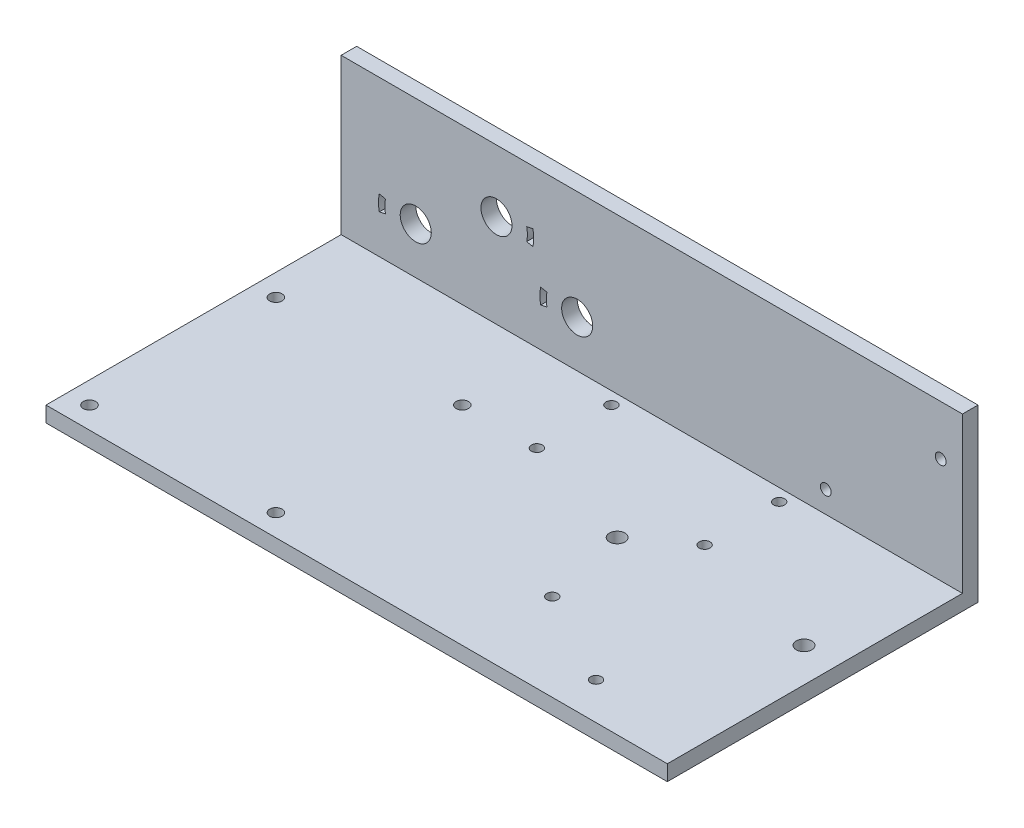
SolidWorks part; units mm, degrees
ref_plane "Front Plane" through (0, 0, 0) normal (0, 0, 1) x (1, 0, 0)
ref_plane "Top Plane" through (0, 0, 0) normal (0, 1, 0) x (1, 0, 0)
ref_plane "Right Plane" through (0, 0, 0) normal (1, 0, 0) x (0, 0, -1)
sketch "Sketch1" plane through (0, 0, 0) normal (0, 1, 0) x (1, 0, 0)
  line L1 (100, -50) -> (-100, -50)
  line L2 (100, -50) -> (100, 50)
  line L3 (100, 50) -> (-100, 50)
  line L4 (-100, -50) -> (-100, 50)
  line L5 (100, -50) -> (-100, 50) construction
  line L6 (100, 50) -> (-100, -50) construction
  point P0 (0, 0)
  dimension "D1" = 200
  dimension "D2" = 100
extrude "Boss-Extrude1" add sketch "Sketch1" along normal blind 5
sketch "Sketch2" plane through (0, 5, 0) normal (0, 1, 0) x (1, 0, 0)
  line L0 (100, -50) -> (100, 50) construction
  line L1 (-100, 50) -> (100, 50)
  line L2 (-100, 50) -> (-100, 45)
  line L3 (-100, 45) -> (100, 45)
  line L4 (100, 50) -> (100, 45)
  dimension "D1" = 5
extrude "Boss-Extrude2" add sketch "Sketch2" along normal blind 50
sketch "Sketch3" plane through (0, 0, -50) normal (0, 0, -1) x (-1, 0, 0)
  line L0 (-93, 12) -> (-56, 39) construction
  line L1 (-93, 39) -> (-56, 39) construction
  line L2 (-93, 39) -> (-93, 12) construction
  line L3 (-93, 12) -> (-56, 12) construction
  line L4 (-56, 39) -> (-56, 12) construction
  line L8 (100, 5) -> (-100, 5) construction
  line L9 (-100, 55) -> (-100, 0) construction
  circle A0 centre (-93, 39) radius 1.75
  circle A1 centre (-56, 12) radius 1.75
  dimension "D3" = 3.5
  dimension "D1" = 27
  dimension "D2" = 37
  dimension "D4" = 7
  dimension "D5" = 7
extrude "Cut-Extrude1" cut sketch "Sketch3" against normal blind 50
sketch "Sketch4" plane through (0, 5, 0) normal (0, 1, 0) x (1, 0, 0)
  line L0 (-100, 45) -> (100, 45) construction
  line L1 (49, -979.2147) -> (49, 49020.7853) construction
  line L2 (100, -50) -> (100, 45) construction
  circle A0 centre (28.85, 5) radius 2.5
  circle A1 centre (89, 5) radius 2.5
  dimension "D1" = 5
  dimension "D2" = 60.15
  dimension "D3" = 40
  dimension "D4" = 40
  dimension "D5" = 51
extrude "Cut-Extrude2" cut sketch "Sketch4" against normal through all
sketch "Sketch7" plane through (0, 5, 0) normal (0, 1, 0) x (1, 0, 0)
  line L0 (-100, -50) -> (100, -50) construction
  line L1 (-93, -43) -> (-33, -43) construction
  line L2 (-93, -43) -> (-93, 17) construction
  line L3 (-93, 17) -> (-33, 17) construction
  line L4 (-33, -43) -> (-33, 17) construction
  line L5 (-93, -43) -> (-33, 17) construction
  line L6 (-93, 17) -> (-33, -43) construction
  line L7 (-100, 45) -> (-100, -50) construction
  circle A0 centre (-93, 17) radius 2
  circle A1 centre (-33, 17) radius 2
  circle A2 centre (-33, -43) radius 2
  circle A3 centre (-93, -43) radius 2
  point P0 (-63, -13)
  dimension "D1" = 4
  dimension "D2" = 60
  dimension "D3" = 7
  dimension "D4" = 7
  dimension "D5" = 60
extrude "Cut-Extrude3" cut sketch "Sketch7" against normal through all
sketch "Sketch8" plane through (0, 5, 0) normal (0, 1, 0) x (1, 0, 0)
  line L0 (-100, -50) -> (100, -50) construction
  line L1 (34.875, -21.92) -> (65.125, -21.92) construction
  line L2 (34.875, -21.92) -> (34.875, -38.08) construction
  line L3 (34.875, -38.08) -> (65.125, -38.08) construction
  line L4 (65.125, -21.92) -> (65.125, -38.08) construction
  line L5 (34.875, -21.92) -> (65.125, -38.08) construction
  line L6 (34.875, -38.08) -> (65.125, -21.92) construction
  line L7 (100, -50) -> (100, 45) construction
  circle A1 centre (65.125, -38.08) radius 1.75
  circle A2 centre (34.875, -21.92) radius 1.75
  point P0 (50, -30)
  dimension "D1" = 3.5
  dimension "D2" = 16.16
  dimension "D3" = 30.25
  dimension "D4" = 20
  dimension "D5" = 50
extrude "Cut-Extrude4" cut sketch "Sketch8" against normal through all
sketch "Sketch11" plane through (0, 0, -45) normal (0, 0, 1) x (1, 0, 0)
  line L0 (-75.9808, 20) -> (-50, 35) construction
  line L1 (-50, 35) -> (-24.0192, 20) construction
  line L2 (-100, 55) -> (-100, 5) construction
  line L3 (-100, 55) -> (100, 55) construction
  line L4 (-1050, 35) -> (48950, 35) construction
  line L5 (-1024.0192, 20) -> (48975.9808, 20) construction
  line L6 (-50, 35) -> (-38.2633, 37.5) construction
  line L7 (-50, 35) -> (-38.2633, 32.5) construction
  line L8 (-24.0192, 20) -> (-35.7559, 22.5) construction
  line L9 (-24.0192, 20) -> (-35.7559, 17.5) construction
  line L10 (-75.9808, 20) -> (-87.7175, 22.5) construction
  line L11 (-75.9808, 20) -> (-87.7175, 17.5) construction
  line L12 (-87.7175, 22.5) -> (-85.7175, 22.074)
  line L13 (-87.7175, 17.5) -> (-85.7175, 17.926)
  line L14 (-40.2633, 37.074) -> (-38.2633, 37.5)
  line L15 (-40.2633, 32.926) -> (-38.2633, 32.5)
  line L16 (-35.7559, 22.5) -> (-33.7559, 22.074)
  line L17 (-35.7559, 17.5) -> (-33.7559, 17.926)
  circle A0 centre (-75.9808, 20) radius 5
  circle A1 centre (-50, 35) radius 5
  circle A2 centre (-24.0192, 20) radius 5
  circle A3 centre (-24.0192, 20) radius 12 construction
  circle A4 centre (-50, 35) radius 12 construction
  circle A5 centre (-75.9808, 20) radius 12 construction
  arc A6 (-38.2633, 37.5) -> (-38.2633, 32.5) centre (-50, 35) cw
  arc A7 (-35.7559, 22.5) -> (-35.7559, 17.5) centre (-24.0192, 20) ccw
  arc A8 (-33.7559, 22.074) -> (-33.7559, 17.926) centre (-24.0192, 20) ccw
  arc A9 (-87.7175, 17.5) -> (-87.7175, 22.5) centre (-75.9808, 20) cw
  arc A10 (-85.7175, 22.074) -> (-85.7175, 17.926) centre (-75.9808, 20) ccw
  arc A11 (-40.2633, 37.074) -> (-40.2633, 32.926) centre (-50, 35) cw
  dimension "D1" = 10
  dimension "D6" = 24
  dimension "D2" = 30
  dimension "D3" = 50
  dimension "D4" = 20
  dimension "D5" = 120
  dimension "D7" = 5
  dimension "D8" = 5
  dimension "D9" = 5
  dimension "D10" = 2
  dimension "D11" = 2
  dimension "D12" = 2
extrude "Cut-Extrude6" cut sketch "Sketch11" against normal through all
sketch "Sketch12" plane through (0, 5, 0) normal (0, 1, 0) x (1, 0, 0)
  line L0 (-100, 45) -> (100, 45) construction
  line L1 (45, 17) -> (-9, 17) construction
  line L2 (45, 17) -> (45, 41) construction
  line L3 (45, 41) -> (-9, 41) construction
  line L4 (-9, 17) -> (-9, 41) construction
  line L5 (45, 17) -> (-9, 41) construction
  line L6 (45, 41) -> (-9, 17) construction
  line L7 (100, -50) -> (100, 45) construction
  circle A0 centre (-9, 41) radius 1.75
  circle A1 centre (45, 41) radius 1.75
  circle A2 centre (-9, 17) radius 1.75
  circle A3 centre (45, 17) radius 1.75
  point P0 (18, 29)
  dimension "D1" = 3.5
  dimension "D3" = 24
  dimension "D2" = 54
  dimension "D4" = 4
  dimension "D5" = 55
extrude "Cut-Extrude7" cut sketch "Sketch12" against normal through all
